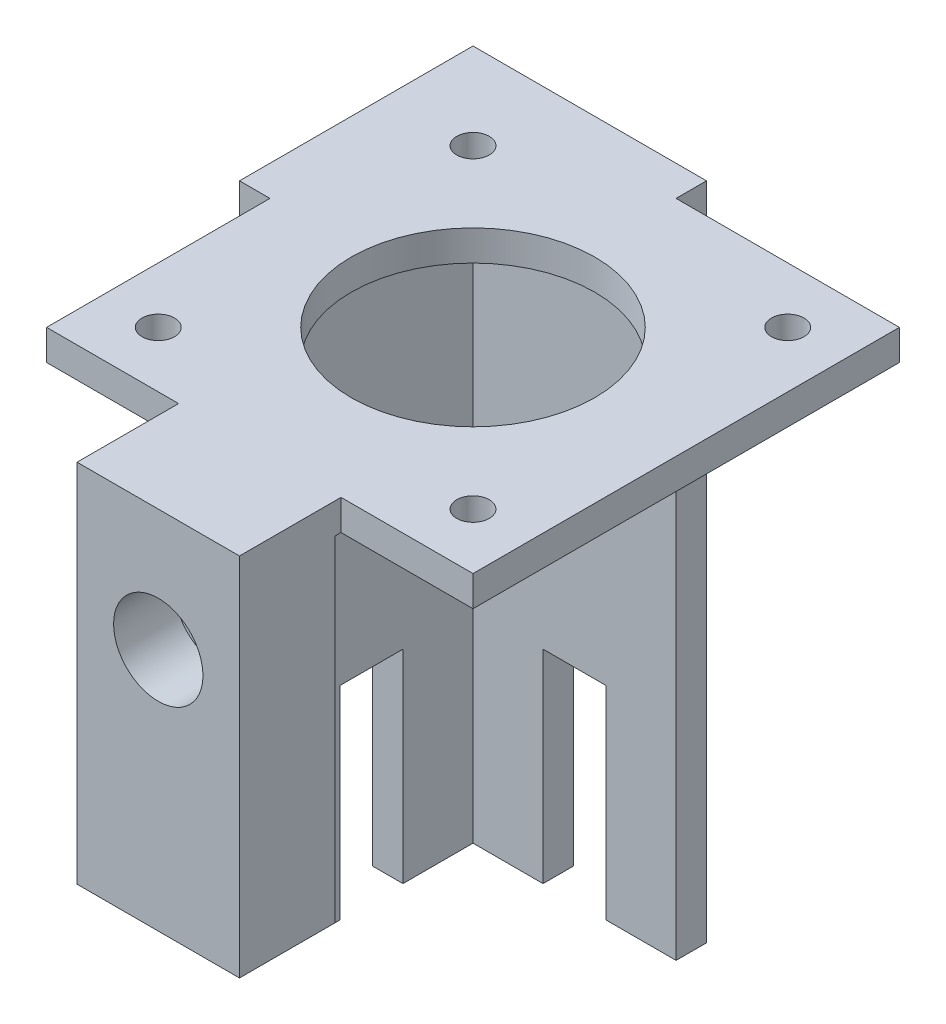
SolidWorks part; units mm, degrees
ref_plane "前视基准面" through (0, 0, 0) normal (0, 0, 1) x (1, 0, 0)
ref_plane "上视基准面" through (0, 0, 0) normal (0, 1, 0) x (1, 0, 0)
ref_plane "右视基准面" through (0, 0, 0) normal (1, 0, 0) x (0, 0, -1)
other "Configuration Table"
sketch "草图1" plane through (0, 0, 0) normal (0, 1, 0) x (1, 0, 0)
  line L1 (-21, -21) -> (21, -21)
  line L2 (-21, -21) -> (-21, 21)
  line L3 (-21, 21) -> (21, 21)
  line L4 (21, -21) -> (21, 21)
  line L5 (0, 21) -> (0, -21) construction
  line L6 (-21, 0) -> (21, 0) construction
  line L7 (-15.5, -15.5) -> (15.5, -15.5) construction
  line L8 (-15.5, -15.5) -> (-15.5, 15.5) construction
  line L9 (-15.5, 15.5) -> (15.5, 15.5) construction
  line L10 (15.5, -15.5) -> (15.5, 15.5) construction
  line L11 (0, 15.5) -> (0, -15.5) construction
  line L12 (-15.5, 0) -> (15.5, 0) construction
  circle A0 centre (15.5, 15.5) radius 1.6
  circle A1 centre (15.5, -15.5) radius 1.6
  circle A2 centre (-15.5, -15.5) radius 1.6
  circle A3 centre (-15.5, 15.5) radius 1.6
  circle A4 centre (0, 0) radius 12
  point P0 (0, 0)
  point P4 (0, 0)
  point P24 (0, 0)
  dimension "D3" = 31
  dimension "D5" = 3.2
  dimension "D7" = 24
  dimension "D1" = 42
  dimension "D2" = 42
  dimension "D4" = 31
  dimension "D6" = 4
extrude "凸台-拉伸1" add sketch "草图1" along normal blind 3
sketch "草图2" plane through (0, 0, 21) normal (0, 0, 1) x (1, 0, 0)
  line L0 (-21, 3) -> (21, 3) construction
  line L1 (8, 3) -> (-8, 3)
  line L2 (8, 3) -> (8, -33)
  line L3 (8, -33) -> (-8, -33)
  line L4 (-8, 3) -> (-8, -33)
  point P6 (0, -33)
  dimension "D1" = 36
  dimension "D2" = 16
extrude "凸台-拉伸2" add sketch "草图2" along normal blind 10
sketch "草图3" plane through (0, 0, 31) normal (0, 0, 1) x (1, 0, 0)
  circle A0 centre (0, -9) radius 4.4
  point P2 (0, 0)
  dimension "D1" = 8.8
  dimension "D2" = 9
extrude "切除-拉伸1" cut sketch "草图3" against normal blind 6
sketch "草图4" plane through (0, 3, 0) normal (0, 1, 0) x (1, 0, 0)
  line L1 (21, 21) -> (-21, 21) construction
  line L16 (21, -21) -> (21, 21) construction
  line L17 (1, 21) -> (21, 21)
  line L18 (1, 21) -> (1, 24)
  line L19 (1, 24) -> (24, 24)
  line L22 (24, 24) -> (24, 1)
  line L23 (24, 1) -> (21, 1)
  line L24 (21, 21) -> (21, 1)
  point P8 (0, 0)
  point P9 (0, 0)
  point P11 (0, 0)
  point P12 (0, 0)
  point P13 (0, 0)
  dimension "D1" = 3
  dimension "D2" = 3
  dimension "D3" = 23
  dimension "D4" = 23
  dimension "D5" = 0
extrude "凸台-拉伸3" add sketch "草图4" against normal blind 65
sketch "草图5" plane through (0, 0, -24) normal (0, 0, -1) x (-1, 0, 0)
  line L0 (-24, -62) -> (-1, -62) construction
  line L1 (-14.1, -62) -> (-7.9, -62)
  line L2 (-14.1, -62) -> (-14.1, -42)
  line L3 (-14.1, -42) -> (-7.9, -42)
  line L4 (-7.9, -62) -> (-7.9, -42)
  line L5 (-24, -62) -> (-24, 3) construction
  dimension "D1" = 9.9
  dimension "D2" = 6.2
  dimension "D3" = 20
extrude "切除-拉伸2" cut sketch "草图5" against normal blind 50
sketch "草图6" plane through (24, 0, 0) normal (1, 0, 0) x (0, 0, -1)
  line L0 (1, -62) -> (24, -62) construction
  line L1 (7.9, -62) -> (14.1, -62)
  line L2 (7.9, -62) -> (7.9, -42)
  line L3 (7.9, -42) -> (14.1, -42)
  line L4 (14.1, -62) -> (14.1, -42)
  line L5 (24, -62) -> (24, 3) construction
  dimension "D1" = 9.9
  dimension "D2" = 6.2
  dimension "D3" = 20
extrude "切除-拉伸3" cut sketch "草图6" against normal up to next
sketch "草图7" plane through (0, -33, 0) normal (0, -1, 0) x (1, 0, 0)
  line L3 (-8, 31) -> (-8, 21) construction
  line L5 (8, 21) -> (-8, 21)
  line L6 (8, 21) -> (8, 21.6)
  line L7 (8, 21.6) -> (-8, 21.6)
  line L8 (-8, 21) -> (-8, 21.6)
  dimension "D1" = 0.6
extrude "切除-拉伸4" cut sketch "草图7" against normal up to surface (33 mm away) up to face at (-15.5, 0, 17.1)
ref_plane "基准面1" through (-31, 0, 0) normal (-1, 0, 0) x (0, 0, 1)
mirror "镜向3" about plane through (-31, 0, 0) normal (-1, 0, 0) of bodies 112
delete or keep bodies "实体-删除/保留 1" type delete bodies bodies 112
